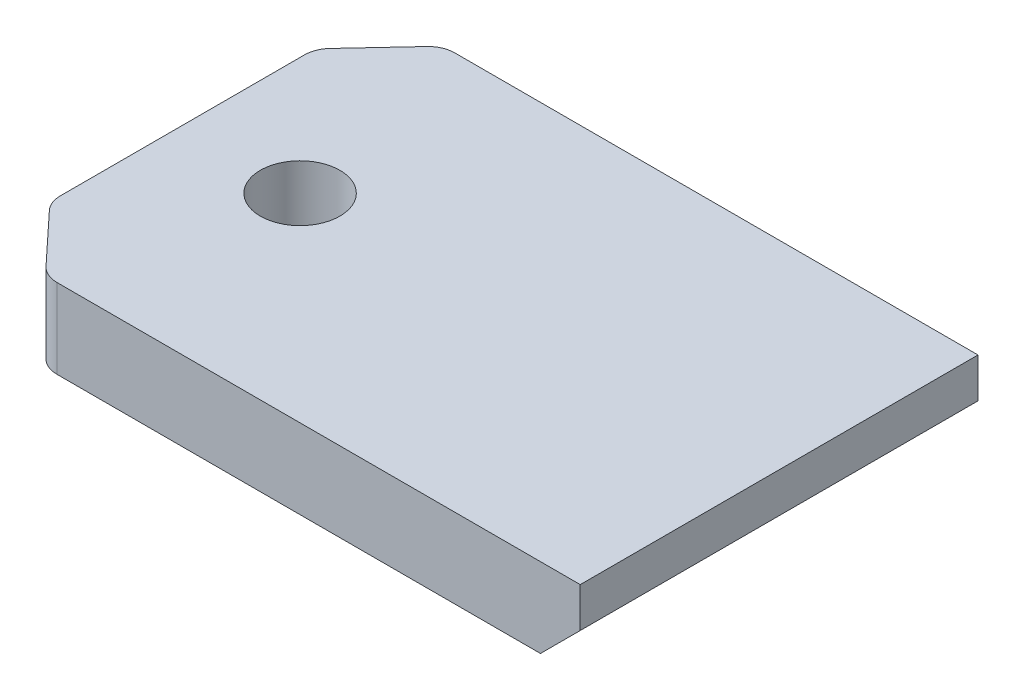
SolidWorks part; units mm, degrees
ref_plane "Спереди" through (0, 0, 0) normal (0, 0, 1) x (1, 0, 0)
ref_plane "Сверху" through (0, 0, 0) normal (0, 1, 0) x (1, 0, 0)
ref_plane "Справа" through (0, 0, 0) normal (1, 0, 0) x (0, 0, -1)
sketch "Эскиз1" plane through (0, 0, 0) normal (1, 0, 0) x (0, 0, -1)
  line L1 (0, 0) -> (30, 0)
  line L2 (0, 0) -> (0, -6)
  line L3 (0, -6) -> (30, -6)
  line L4 (30, 0) -> (30, -6)
extrude "Вытянуть1" add sketch "Эскиз1" along normal blind 45
chamfer "Фаска1" distance 3 angle 45 1 edges at (45, -6, -15)
sketch "Эскиз2" plane through (0, 0, 0) normal (0, 1, 0) x (-1, 0, 0)
  line L0 (-10.5597, -15) -> (-7.257, -15) construction
  circle A0 centre (-8.8699, -15) radius 3
extrude "Вырез-Вытянуть1" cut sketch "Эскиз2" against normal through all
chamfer "Фаска2" distance 5 angle 43 2 edges at (0, -3, -30) (0, -3, 0)
fillet "Скругление1" radius 2 4 edges at (4.6626, -3, 0) (0, -3, -5) (0, -3, -25) (4.6626, -3, -30)
